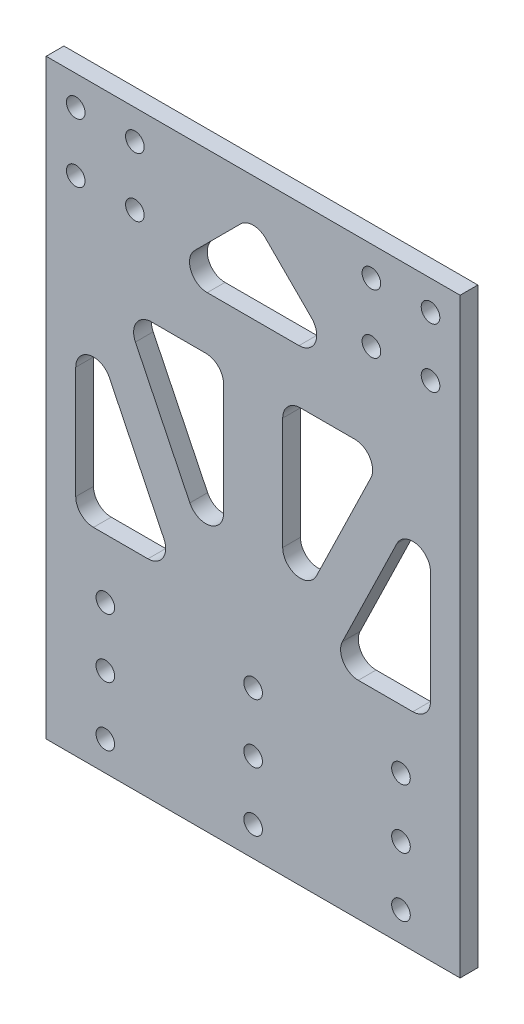
SolidWorks part; units mm, degrees
ref_plane "前视基准面" through (0, 0, 0) normal (0, 0, 1) x (1, 0, 0)
ref_plane "上视基准面" through (0, 0, 0) normal (0, 1, 0) x (1, 0, 0)
ref_plane "右视基准面" through (0, 0, 0) normal (1, 0, 0) x (0, 0, -1)
other "Configuration Table"
sketch "草图1" plane through (0, 0, 0) normal (0, 0, 1) x (1, 0, 0)
  line L1 (0, 0) -> (70, 0)
  line L2 (0, 0) -> (0, -100)
  line L3 (0, -100) -> (70, -100)
  line L4 (70, 0) -> (70, -100)
  dimension "D1" = 70
  dimension "D2" = 100
extrude "凸台-拉伸1" add sketch "草图1" along normal blind 3
sketch "草图2" plane through (0, 0, 3) normal (0, 0, 1) x (1, 0, 0)
  line L0 (35, 0) -> (35, -100) construction
  line L1 (70, 0) -> (0, 0) construction
  line L2 (0, -100) -> (70, -100) construction
  line L3 (0, -10) -> (70, -10) construction
  line L4 (0, 0) -> (0, -100) construction
  line L5 (70, -100) -> (70, 0) construction
  line L6 (10, 0) -> (10, -10) construction
  line L7 (0, -85) -> (70, -85) construction
  line L8 (0, -80) -> (70, -80) construction
  circle A0 centre (5, -5) radius 1.575
  circle A1 centre (15, -5) radius 1.575
  circle A2 centre (15, -15) radius 1.575
  circle A3 centre (5, -15) radius 1.575
  circle A4 centre (65, -15) radius 1.575
  circle A5 centre (55, -15) radius 1.575
  circle A6 centre (55, -5) radius 1.575
  circle A7 centre (65, -5) radius 1.575
  circle A8 centre (10, -85) radius 1.575
  circle A9 centre (35, -85) radius 1.575
  circle A10 centre (60, -85) radius 1.575
  circle A11 centre (60, -75) radius 1.575
  circle A12 centre (35, -75) radius 1.575
  circle A13 centre (10, -75) radius 1.575
  circle A14 centre (10, -95) radius 1.575
  circle A15 centre (35, -95) radius 1.575
  circle A16 centre (60, -95) radius 1.575
  dimension "D1" = 3.15
  dimension "D7" = 3.15
  dimension "D9" = 3.15
  dimension "D2" = 10
  dimension "D3" = 5
  dimension "D4" = 5
  dimension "D5" = 10
  dimension "D6" = 15
  dimension "D8" = 10
  dimension "D10" = 5
extrude "切除-拉伸1" cut sketch "草图2" against normal through all
sketch "草图3" plane through (0, 0, 0) normal (0, 0, -1) x (-1, 0, 0)
  line L0 (-65, -30) -> (-65, -65)
  line L1 (-65, -65) -> (-48, -65)
  line L2 (-48, -65) -> (-65, -30)
  line L3 (-57, -30) -> (-40, -65)
  line L4 (-40, -65) -> (-40, -30)
  line L5 (-40, -30) -> (-57, -30)
  line L6 (-35, 0) -> (-35, -100) construction
  line L7 (-70, 0) -> (0, 0) construction
  line L8 (0, -100) -> (-70, -100) construction
  line L9 (-70, -100) -> (-70, 0) construction
  line L10 (-30, -30) -> (-13, -30)
  line L11 (-30, -65) -> (-30, -30)
  line L12 (-13, -30) -> (-30, -65)
  line L13 (-22, -65) -> (-5, -30)
  line L14 (-5, -65) -> (-22, -65)
  line L15 (-5, -30) -> (-5, -65)
  line L16 (-35, -6) -> (-50, -21)
  line L17 (-50, -21) -> (-20, -21)
  line L18 (-20, -21) -> (-35, -6)
  point P12 (-22, -18.5696)
  point P24 (-46.9298, -19.6402)
  point P25 (0, 0)
  point P26 (0, 0)
  point P27 (-35, -5.5712)
  dimension "D1" = 17
  dimension "D2" = 35
  dimension "D3" = 35
  dimension "D4" = 17
  dimension "D5" = 35
  dimension "D6" = 30
  dimension "D7" = 5
  dimension "D8" = 5
  dimension "D9" = 30
  dimension "D10" = 6
extrude "切除-拉伸2" cut sketch "草图3" against normal through all
fillet "圆角2" radius 3 15 edges at (5, -30, 1.5) (22, -65, 1.5) (5, -65, 1.5) (13, -30, 1.5) (30, -30, 1.5) (30, -65, 1.5) (40, -65, 1.5) (40, -30, 1.5) (57, -30, 1.5) (65, -30, 1.5) (65, -65, 1.5) (48, -65, 1.5) (35, -6, 1.5) (50, -21, 1.5) (20, -21, 1.5)
